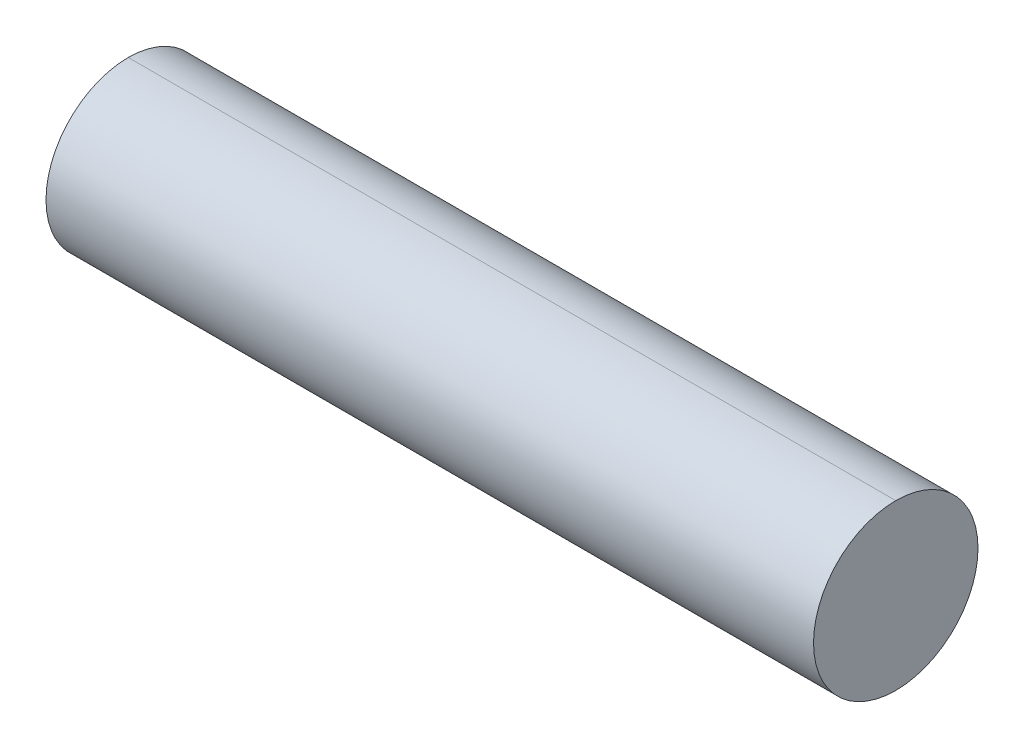
SolidWorks part; units mm, degrees
material "AISI 4340 Steel, normalized"
ref_plane "Front Plane" through (0, 0, 0) normal (0, 0, 1) x (1, 0, 0)
ref_plane "Top Plane" through (0, 0, 0) normal (0, 1, 0) x (1, 0, 0)
ref_plane "Right Plane" through (0, 0, 0) normal (1, 0, 0) x (0, 0, -1)
sketch "Sketch1" plane through (0, 0, 0) normal (1, 0, 0) x (0, 0, -1)
  circle A0 centre (0, 0) radius 19.05
  dimension "D1" = 38.1
extrude "Boss-Extrude1" add sketch "Sketch1" along normal blind 177.8
split line "Split Line1"
scale "Scale1" scale about centroid uniform scaling yes scale factor 2.84
